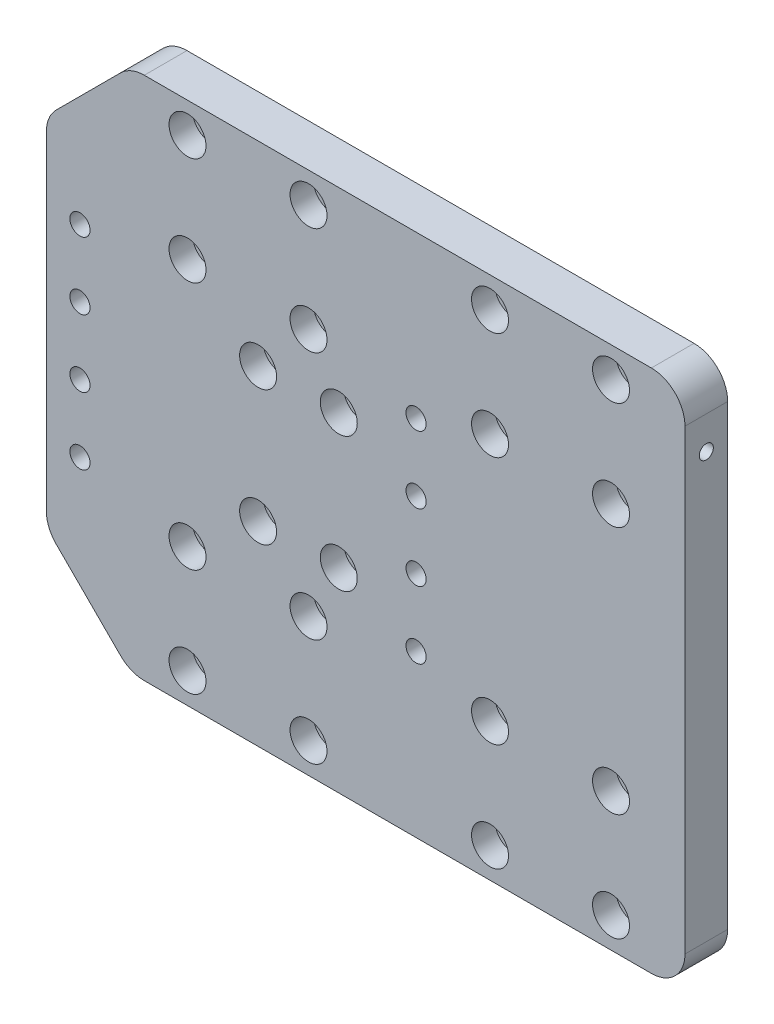
SolidWorks part; units mm, degrees
ref_plane "Front Plane" through (0, 0, 0) normal (0, 0, 1) x (1, 0, 0)
ref_plane "Top Plane" through (0, 0, 0) normal (0, 1, 0) x (1, 0, 0)
ref_plane "Right Plane" through (0, 0, 0) normal (1, 0, 0) x (0, 0, -1)
sketch "Sketch1" plane through (0, 0, 0) normal (0, 0, 1) x (1, 0, 0)
  line L0 (0, -78) -> (0, 78) construction
  line L1 (-85, 78) -> (85, 78)
  line L2 (-85, 78) -> (-85, -78) construction
  line L3 (-85, -78) -> (85, -78)
  line L4 (85, 78) -> (85, -78)
  line L5 (-85, 53) -> (85, 53) construction
  line L6 (-85, -53) -> (85, -53) construction
  line L7 (-85, 0) -> (85, 0) construction
  line L8 (27, -37) -> (63, -37) construction
  line L9 (27, -37) -> (27, -69) construction
  line L10 (27, -69) -> (63, -69) construction
  line L11 (63, -37) -> (63, -69) construction
  line L12 (27, -37) -> (63, -69) construction
  line L13 (27, -69) -> (63, -37) construction
  line L14 (-85, 78) -> (-105, 78)
  line L15 (-42, 20) -> (-18, 20) construction
  line L16 (-42, 20) -> (-42, -20) construction
  line L17 (-42, -20) -> (-18, -20) construction
  line L18 (-18, 20) -> (-18, -20) construction
  line L19 (-42, 20) -> (-18, -20) construction
  line L20 (-42, -20) -> (-18, 20) construction
  line L21 (-105, 78) -> (-105, -78)
  line L22 (-105, -78) -> (-85, -78)
  line L24 (-106, -26) -> (85.5, -26) construction
  line L25 (-106, -26) -> (-106, 26) construction
  line L26 (-106, 26) -> (85.5, 26) construction
  line L27 (85.5, -26) -> (85.5, 26) construction
  line L28 (-10.25, 26) -> (-10.25, -26) construction
  line L29 (-106, 0) -> (85.5, 0) construction
  circle A0 centre (27, -37) radius 2.5
  circle A1 centre (63, -37) radius 2.5
  circle A2 centre (27, -69) radius 2.5
  circle A3 centre (63, -69) radius 2.5
  circle A4 centre (-63, -37) radius 2.5
  circle A5 centre (-63, -69) radius 2.5
  circle A6 centre (-27, -69) radius 2.5
  circle A7 centre (-27, -37) radius 2.5
  circle A8 centre (63, 69) radius 2.5
  circle A9 centre (63, 37) radius 2.5
  circle A10 centre (27, 69) radius 2.5
  circle A11 centre (27, 37) radius 2.5
  circle A12 centre (-27, 69) radius 2.5
  circle A13 centre (-27, 37) radius 2.5
  circle A14 centre (-63, 69) radius 2.5
  circle A15 centre (-63, 37) radius 2.5
  circle A16 centre (-42, 20) radius 2.5
  circle A17 centre (-18, 20) radius 2.5
  circle A18 centre (-42, -20) radius 2.5
  circle A19 centre (-18, -20) radius 2.5
  point P11 (45, -53)
  point P47 (-30, 0)
  point P56 (-30, 0)
  dimension "D3" = 5
  dimension "D1" = 106
  dimension "D2" = 170
  dimension "D4" = 36
  dimension "D5" = 32
  dimension "D6" = 45
  dimension "D7" = 25
  dimension "D8" = 25
  dimension "D9" = 24
  dimension "D10" = 40
  dimension "D11" = 1
  dimension "D12" = 20
  dimension "D13" = 1
  dimension "D14" = 52
  dimension "D15" = 75
extrude "Boss-Extrude1" add sketch "Sketch1" along normal blind 12.7
sketch "Sketch2" plane through (0, 0, 12.7) normal (0, 0, 1) x (1, 0, 0)
  circle A0 centre (-63, 69) radius 5.5
  circle A1 centre (-27, 69) radius 5.5
  circle A2 centre (-63, 37) radius 5.5
  circle A3 centre (-27, 37) radius 5.5
  circle A4 centre (27, 69) radius 5.5
  circle A5 centre (63, 69) radius 5.5
  circle A6 centre (27, 37) radius 5.5
  circle A7 centre (63, 37) radius 5.5
  circle A8 centre (-42, 20) radius 5.5
  circle A9 centre (-18, 20) radius 5.5
  circle A10 centre (-42, -20) radius 5.5
  circle A11 centre (-18, -20) radius 5.5
  circle A12 centre (-63, -37) radius 5.5
  circle A13 centre (-27, -37) radius 5.5
  circle A14 centre (-63, -69) radius 5.5
  circle A15 centre (-27, -69) radius 5.5
  circle A16 centre (27, -69) radius 5.5
  circle A17 centre (27, -37) radius 5.5
  circle A18 centre (63, -37) radius 5.5
  circle A19 centre (63, -69) radius 5.5
  dimension "D1" = 11
extrude "Cut-Extrude1" cut sketch "Sketch2" against normal blind 7
sketch "Sketch3" plane through (0, 0, 12.7) normal (0, 0, 1) x (1, 0, 0)
  line L0 (-95, 78) -> (-95, -78) construction
  line L1 (85, 78) -> (-105, 78) construction
  line L2 (-105, -78) -> (85, -78) construction
  line L3 (-105, 78) -> (-105, -78) construction
  line L4 (-95, 0) -> (85, 0) construction
  line L5 (85, -78) -> (85, 78) construction
  circle A0 centre (-95, 30) radius 3
  circle A1 centre (-95, 10) radius 3
  circle A2 centre (-95, -10) radius 3
  circle A3 centre (-95, -30) radius 3
  circle A4 centre (5, -30) radius 3
  circle A5 centre (5, -10) radius 3
  circle A6 centre (5, 10) radius 3
  circle A7 centre (5, 30) radius 3
  point P8 (-95, -10)
  point P9 (-95, -30)
  point P10 (-95, 0)
  point P11 (-95, 10)
  point P12 (-95, 30)
  dimension "D4" = 6
  dimension "D6" = 100
  dimension "D1" = 10
  dimension "D2" = 10
  dimension "D3" = 20
  dimension "D5" = 2
extrude "Cut-Extrude2" cut sketch "Sketch3" against normal up to next
sketch "Sketch4" plane through (0, 0, 0) normal (0, 0, -1) x (-1, 0, 0)
  circle A0 centre (-5, 30) radius 5.5
  circle A1 centre (-5, 10) radius 5.5
  circle A2 centre (-5, -10) radius 5.5
  circle A3 centre (-5, -30) radius 5.5
  circle A4 centre (95, 30) radius 5.5
  circle A5 centre (95, 10) radius 5.5
  circle A6 centre (95, -10) radius 5.5
  circle A7 centre (95, -30) radius 5.5
  dimension "D1" = 11
extrude "Cut-Extrude3" cut sketch "Sketch4" against normal blind 7
chamfer "Chamfer1" distance 25 angle 45 2 edges at (-105, 78, 6.35) (-105, -78, 6.35)
fillet "Fillet1" radius 10 6 edges at (85, 78, 6.35) (85, -78, 6.35) (-80, -78, 6.35) (-105, -53, 6.35) (-105, 53, 6.35) (-80, 78, 6.35)
sketch "Sketch5" plane through (85, 0, 0) normal (1, 0, 0) x (0, 0, -1)
  line L0 (-6.35, 78) -> (-6.35, 58.25) construction
  line L1 (-12.7, 78) -> (0, 78) construction
  dimension "D1" = 19.75
hole_wizard "M5x0.8 Tapped Hole1" positions "Sketch6" profile "Sketch7" tap size "M5x0.8" standard "ANSI Metric"
sketch "Sketch6" plane through (85, 0, 0) normal (1, 0, 0) x (0, 0, -1)
  point P0 (-6.35, 58.25)
sketch "Sketch7" plane through (85, 58.25, 6.35) normal (0, 1, 0) x (0, 0, -1)
  line L0 (0, 0) -> (0, 20.2618)
  line L1 (0, 20.2618) -> (2.1, 19)
  line L2 (2.1, 19) -> (2.1, 0)
  line L5 (2.1, 0) -> (0, 0)
  line L10 (0, 20.2618) -> (-2.1, 19) construction
  line L11 (0, -6.35) -> (0, 107.95) construction
  dimension "Tap Drill Dia." = 4.2
  dimension "Tap Drill Depth" = 19
  dimension "Drill Angle" = 118
cosmetic thread "Hole Thread1" parameters "D1"=15, "D2"=5
